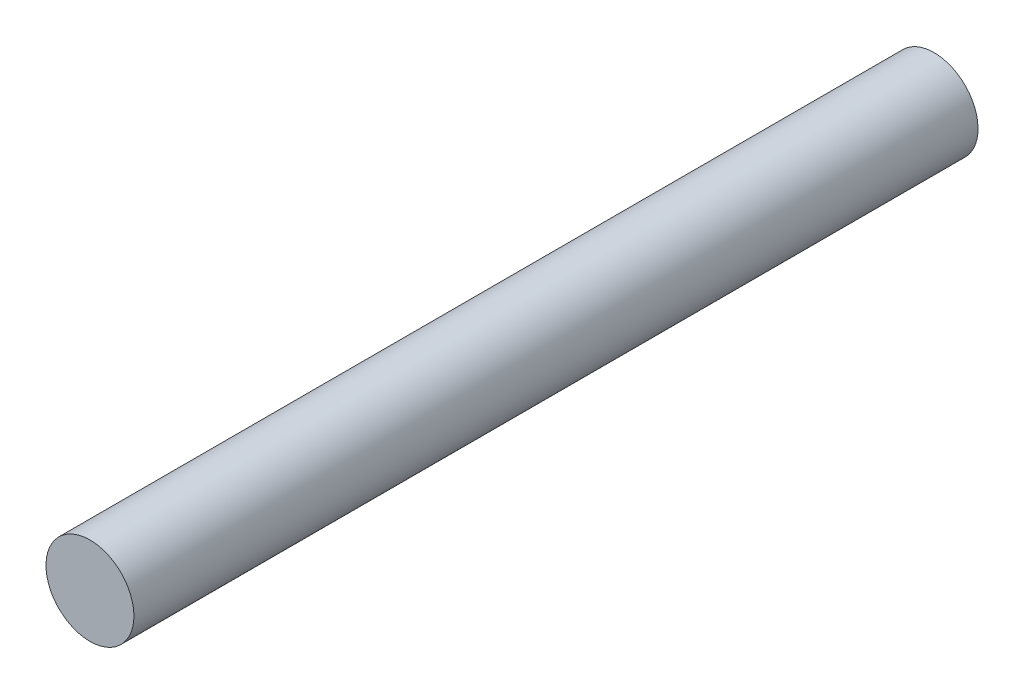
SolidWorks part; units mm, degrees
ref_plane "Front Plane" through (0, 0, 0) normal (0, 0, 1) x (1, 0, 0)
ref_plane "Top Plane" through (0, 0, 0) normal (0, 1, 0) x (1, 0, 0)
ref_plane "Right Plane" through (0, 0, 0) normal (1, 0, 0) x (0, 0, -1)
sketch "Sketch2" plane through (-89.7431, 20.5949, 187.198) normal (0, 0, -1) x (-0.9718, -0.2359, 0)
  arc A1 (65.3129, 61.8708) -> (47.1834, 83.9252) centre (56.2481, 72.898) ccw construction
  circle A2 centre (236.3612, 72.898) radius 19.05
  dimension "D1" = 38.1
extrude "Boss-Extrude1" add sketch "Sketch2" along normal mid plane 365.76
